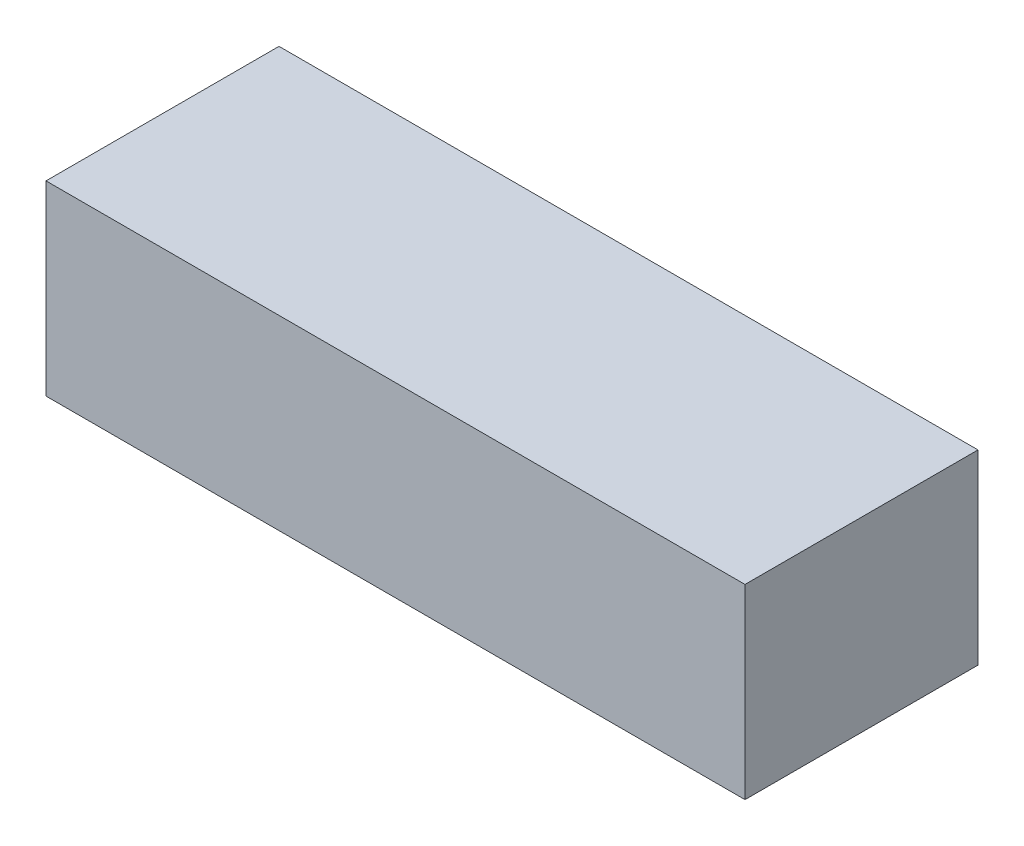
SolidWorks part; units mm, degrees
ref_plane "Front Plane" through (0, 0, 0) normal (0, 0, 1) x (1, 0, 0)
ref_plane "Top Plane" through (0, 0, 0) normal (0, 1, 0) x (1, 0, 0)
ref_plane "Right Plane" through (0, 0, 0) normal (1, 0, 0) x (0, 0, -1)
other "Bounding Box"
ref_plane "Default Plane" through (-8.9266, -12.7485, 0) normal (-0.1736, 0.9848, 0) x (0.9848, 0.1736, 0)
sketch "Sketch1" plane through (0, 0, 0) normal (0, 1, 0) x (1, 0, 0)
  line L1 (38.1, -12.7) -> (-38.1, -12.7)
  line L2 (38.1, -12.7) -> (38.1, 12.7)
  line L3 (38.1, 12.7) -> (-38.1, 12.7)
  line L4 (-38.1, -12.7) -> (-38.1, 12.7)
  line L5 (38.1, -12.7) -> (-38.1, 12.7) construction
  line L6 (38.1, 12.7) -> (-38.1, -12.7) construction
  point P0 (0, 0)
  dimension "D1" = 25.4
  dimension "D2" = 76.2
extrude "Boss-Extrude1" add sketch "Sketch1" along normal blind 20.32
